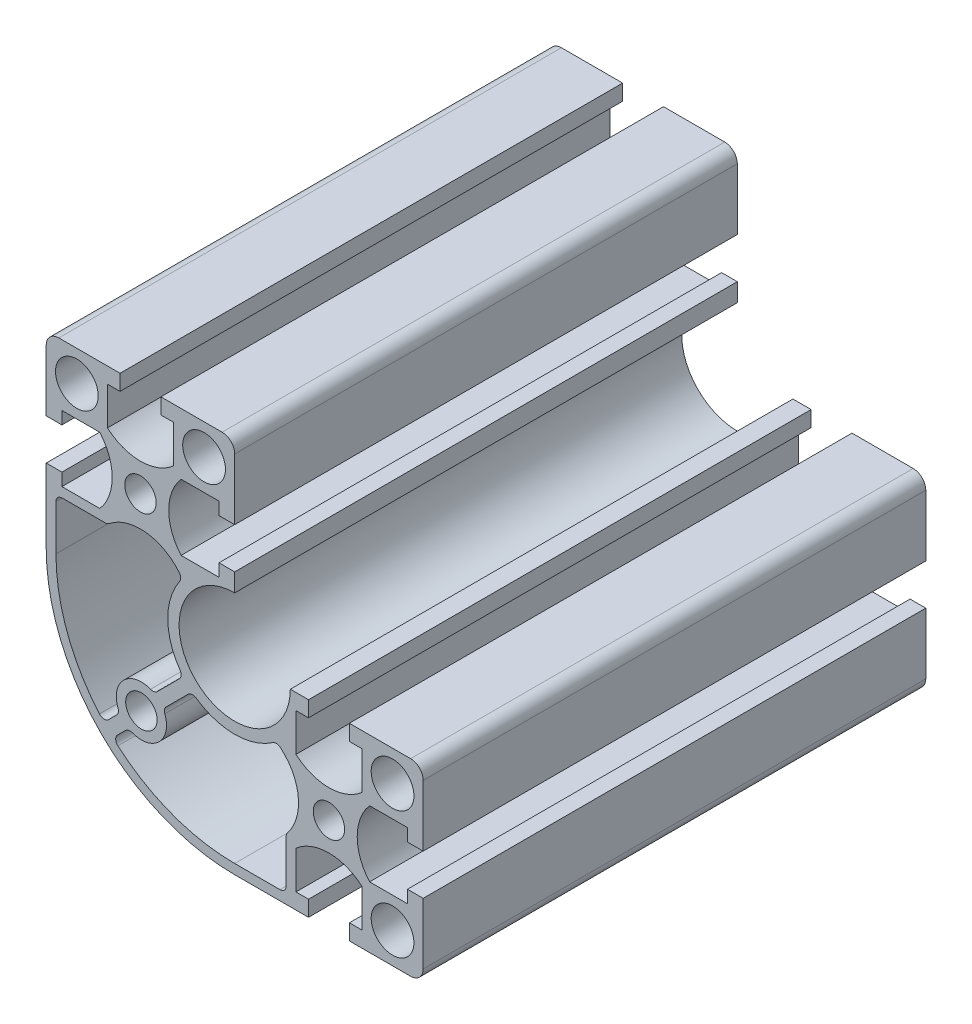
SolidWorks part; units mm, degrees
material "6061 Alaşım"
ref_plane "Ön Düzlem" through (0, 0, 0) normal (0, 0, 1) x (1, 0, 0)
ref_plane "Üst Düzlem" through (0, 0, 0) normal (0, 1, 0) x (1, 0, 0)
ref_plane "Sağ Düzlem" through (0, 0, 0) normal (1, 0, 0) x (0, 0, -1)
sketch "Çizim1" plane through (0, 0, 0) normal (0, 0, 1) x (1, 0, 0)
  line L0 (18.25, 0) -> (30, 0)
  line L1 (30, -30) -> (-30, -30) construction
  line L2 (30, -30) -> (30, 30) construction
  line L3 (30, 30) -> (-30, 30) construction
  line L4 (-30, -30) -> (-30, 30) construction
  line L5 (30, -30) -> (-30, 30) construction
  line L6 (30, 30) -> (-30, -30) construction
  line L7 (24.125, 0) -> (24.125, -9.75) construction
  line L8 (18.25, 0) -> (18.25, -2.5)
  line L9 (18.25, -2.5) -> (20.25, -2.5)
  line L10 (20.25, -2.5) -> (20.25, -8.5363)
  line L11 (9.75, -8.5363) -> (9.75, -2.5)
  line L12 (9.75, -2.5) -> (11.75, -2.5)
  line L13 (11.75, -2.5) -> (11.75, 0)
  line L14 (11.75, 0) -> (8.85, 0)
  line L15 (30, -11.75) -> (27.5, -11.75)
  line L16 (27.5, -11.75) -> (27.5, -9.75)
  line L17 (27.5, -9.75) -> (21.4637, -9.75)
  line L18 (21.4637, -20.25) -> (27.5, -20.25)
  line L19 (27.5, -20.25) -> (27.5, -18.25)
  line L20 (27.5, -18.25) -> (30, -18.25)
  line L21 (27.5, -11.75) -> (27.5, -18.25) construction
  line L22 (20.25, -5.5182) -> (30, -5.5182) construction
  line L23 (11.75, -27.5) -> (18.25, -27.5) construction
  line L24 (18.25, -27.5) -> (18.25, -30)
  line L25 (20.25, -27.5) -> (18.25, -27.5)
  line L26 (20.25, -21.4637) -> (20.25, -27.5)
  line L27 (9.75, -27.5) -> (9.75, -21.4637)
  line L28 (11.75, -27.5) -> (9.75, -27.5)
  line L29 (11.75, -30) -> (11.75, -27.5)
  line L30 (30, 0) -> (30, -11.75)
  line L31 (30, -18.25) -> (30, -30)
  line L32 (30, -30) -> (18.25, -30)
  line L33 (11.75, -30) -> (0, -30)
  line L34 (-17.3825, -18.7967) -> (-18.6514, -20.0656)
  line L35 (-10.9018, -12.316) -> (-7.4084, -8.8226)
  line L36 (0, -28.45) -> (7.2, -28.45)
  line L37 (-6.2579, -6.2579) -> (-21.2132, -21.2132) construction
  line L38 (8.2, -20.6116) -> (8.2, -27.45)
  line L39 (-21.2132, -21.2132) -> (-16.617, -16.617)
  line L40 (-6.2579, -6.2579) -> (-13.0815, -13.0815)
  line L41 (-12.316, -10.9018) -> (-8.8226, -7.4084)
  line L42 (-18.7967, -17.3825) -> (-20.0656, -18.6514)
  line L43 (-28.45, 0) -> (-28.45, 7.2)
  line L44 (-20.6116, 8.2) -> (-27.45, 8.2)
  line L45 (0, 11.75) -> (0, 8.85)
  line L46 (-2.5, 11.75) -> (0, 11.75)
  line L47 (-2.5, 9.75) -> (-2.5, 11.75)
  line L48 (-8.5363, 9.75) -> (-2.5, 9.75)
  line L49 (-2.5, 20.25) -> (-8.5363, 20.25)
  line L50 (-2.5, 18.25) -> (-2.5, 20.25)
  line L51 (0, 18.25) -> (-2.5, 18.25)
  line L52 (0, 18.25) -> (0, 30)
  line L53 (0, 30) -> (-11.75, 30)
  line L54 (-11.75, 30) -> (-11.75, 27.5)
  line L55 (-11.75, 27.5) -> (-9.75, 27.5)
  line L56 (-9.75, 27.5) -> (-9.75, 21.4637)
  line L57 (-20.25, 21.4637) -> (-20.25, 27.5)
  line L58 (-20.25, 27.5) -> (-18.25, 27.5)
  line L59 (-18.25, 27.5) -> (-18.25, 30)
  line L60 (-18.25, 30) -> (-30, 30)
  line L61 (-30, 30) -> (-30, 18.25)
  line L62 (-27.5, 18.25) -> (-30, 18.25)
  line L63 (-27.5, 20.25) -> (-27.5, 18.25)
  line L64 (-21.4637, 20.25) -> (-27.5, 20.25)
  line L65 (-27.5, 9.75) -> (-21.4637, 9.75)
  line L66 (-27.5, 11.75) -> (-27.5, 9.75)
  line L67 (-30, 11.75) -> (-27.5, 11.75)
  line L68 (-30, 11.75) -> (-30, 0)
  arc A0 (20.25, -8.5363) -> (9.75, -8.5363) centre (15, -2.5) cw
  circle A1 centre (0, 0) radius 8.85 construction
  arc A2 (21.4637, -9.75) -> (21.4637, -20.25) centre (27.5, -15) ccw
  circle A3 centre (25.125, -4.875) radius 3.4
  circle A4 centre (25.125, -25.125) radius 3.4
  arc A5 (9.75, -21.4637) -> (20.25, -21.4637) centre (15, -27.5) cw
  circle A6 centre (15, -15) radius 2.5
  circle A7 centre (0, 0) radius 10.65 construction
  circle A8 centre (0, 0) radius 30 construction
  arc A9 (-30, 0) -> (0, -30) centre (0, 0) ccw
  circle A10 centre (-14.8492, -14.8492) radius 2.5 construction
  circle A11 centre (-14.8492, -14.8492) radius 4 construction
  arc A12 (-16.3102, -18.5729) -> (-11.1256, -13.3883) centre (-14.8492, -14.8492) ccw
  arc A13 (0, -28.45) -> (-18.598, -21.5295) centre (0, 0) cw
  arc A14 (-6.1261, -8.7117) -> (6.0425, -8.7699) centre (0, 0) ccw
  arc A15 (8.4182, -19.9881) -> (7.245, -8.821) centre (2.1637, -15) ccw
  arc A16 (0, 8.85) -> (8.85, 0) centre (0, 0) ccw
  arc A17 (7.2, -28.45) -> (8.2, -27.45) centre (7.2, -27.45) ccw
  arc A18 (8.2, -20.6116) -> (8.4182, -19.9881) centre (9.2, -20.6116) cw
  arc A19 (6.0425, -8.7699) -> (7.245, -8.821) centre (6.6098, -9.5934) cw
  arc A20 (-7.4084, -8.8226) -> (-6.1261, -8.7117) centre (-6.7013, -9.5297) cw
  arc A21 (-11.1256, -13.3883) -> (-10.9018, -12.316) centre (-10.1947, -13.0231) cw
  arc A22 (-16.3102, -18.5729) -> (-17.3825, -18.7967) centre (-16.6754, -19.5038) ccw
  arc A23 (-18.6514, -20.0656) -> (-18.598, -21.5295) centre (-17.9443, -20.7727) ccw
  circle A24 centre (-14.8492, -14.8492) radius 2.5
  circle A25 centre (-4.875, 25.125) radius 3.4
  circle A26 centre (-25.125, 25.125) radius 3.4
  circle A27 centre (-15, 15) radius 2.5
  arc A28 (-13.3883, -11.1256) -> (-12.316, -10.9018) centre (-13.0231, -10.1947) ccw
  arc A29 (-18.5729, -16.3102) -> (-13.3883, -11.1256) centre (-14.8492, -14.8492) cw
  arc A30 (-18.5729, -16.3102) -> (-18.7967, -17.3825) centre (-19.5038, -16.6754) cw
  arc A31 (-20.0656, -18.6514) -> (-21.5295, -18.598) centre (-20.7727, -17.9443) cw
  arc A32 (-28.45, 0) -> (-21.5295, -18.598) centre (0, 0) ccw
  arc A33 (-28.45, 7.2) -> (-27.45, 8.2) centre (-27.45, 7.2) cw
  arc A34 (-20.6116, 8.2) -> (-19.9881, 8.4182) centre (-20.6116, 9.2) ccw
  arc A35 (-19.9881, 8.4182) -> (-8.821, 7.245) centre (-15, 2.1637) cw
  arc A36 (-8.7699, 6.0425) -> (-8.821, 7.245) centre (-9.5934, 6.6098) ccw
  arc A37 (-8.8226, -7.4084) -> (-8.7117, -6.1261) centre (-9.5297, -6.7013) ccw
  arc A38 (-8.7117, -6.1261) -> (-8.7699, 6.0425) centre (0, 0) cw
  arc A39 (-8.5363, 20.25) -> (-8.5363, 9.75) centre (-2.5, 15) ccw
  arc A40 (-9.75, 21.4637) -> (-20.25, 21.4637) centre (-15, 27.5) cw
  arc A41 (-21.4637, 9.75) -> (-21.4637, 20.25) centre (-27.5, 15) ccw
  point P0 (0, 0)
  point P23 (27.5, -15)
  point P33 (25.125, -5.5182)
  point P34 (24.125, -4.875)
  point P75 (8.2, -20.25)
  point P78 (6.6107, -8.3499)
  point P81 (-6.7903, -8.2045)
  point P84 (-11.4035, -12.8177)
  point P87 (-16.8807, -18.295)
  dimension "D9" = 2.5
  dimension "D10" = 2.5
  dimension "D14" = 8
  dimension "D15" = 8
  dimension "D16" = 6.8
  dimension "D17" = 6.8
  dimension "D19" = 17.7
  dimension "D20" = 5
  dimension "D21" = 21.3
  dimension "D22" = 60
  dimension "D23" = 5
  dimension "D24" = 8
  dimension "D27" = 1.55
  dimension "D29" = 8
  dimension "D30" = 1
  dimension "D1" = 60
  dimension "D2" = 60
  dimension "D3" = 6.5
  dimension "D4" = 10.5
  dimension "D6" = 15
  dimension "D7" = 2.5
  dimension "D8" = 2.5
  dimension "D11" = 2
  dimension "D12" = 6.5
  dimension "D13" = 15
  dimension "D18" = 9.75
  dimension "D26" = 2
  dimension "D28" = 21.8
extrude "Yükseklik-Ekstrüzyon1" add sketch "Çizim1" along normal blind 80 contours A41 L65 L66 L67 L68 A9 L39 A24 L40 A16 L45 L46 L47 L48 A39 L49 L50 L51 L52 L53 L54 L55 L56 A40 L57 L58 L59 L60 L61 L62 L63 L64 A38 A37 L41 A28 A29 A30 L42 A31 A32 L43 A33 L44 A34 A35 A36 A26 | A24 L39 A9 L33 L29 L28 L27 A5 L26 L25 L24 L32 L31 L20 L19 L18 A2 L17 L16 L15 L30 L0 L8 L9 L10 A0 L11 L12 L13 L14 A16 L40 A23 L34 A22 A12 A21 L35 A20 A14 A19 A15 A18 L38 A17 L36 A13 A6
fillet "Fillet1" radius 2 4 edges at (30, -30, 40) (30, 0, 40) (0, 30, 40) (-30, 30, 40)
